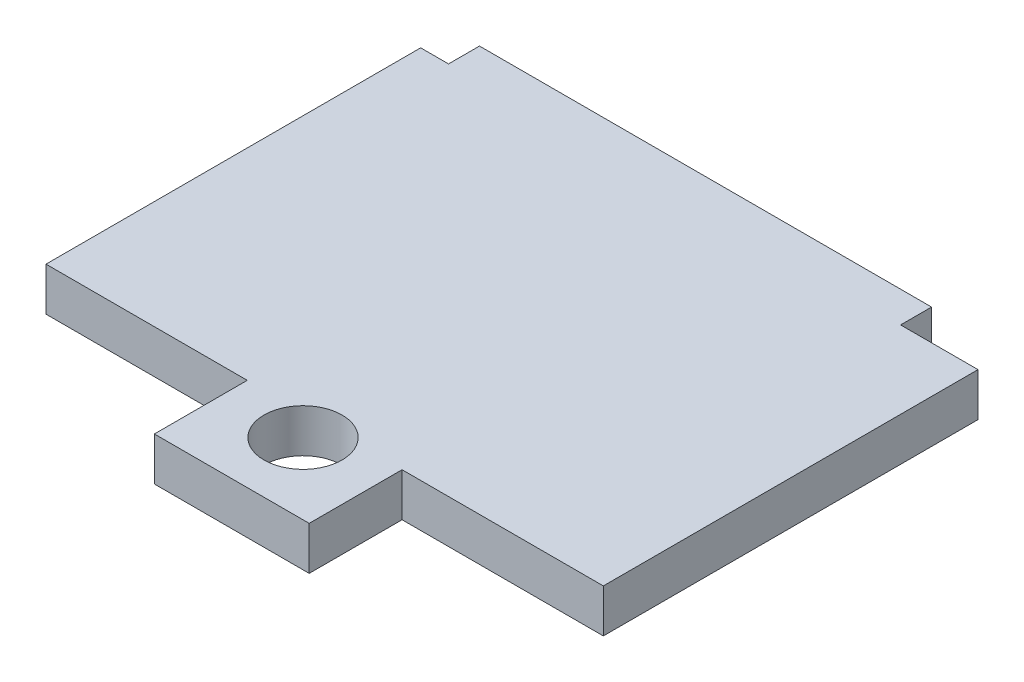
SolidWorks part; units mm, degrees
ref_plane "Front Plane" through (0, 0, 0) normal (0, 0, 1) x (1, 0, 0)
ref_plane "Top Plane" through (0, 0, 0) normal (0, 1, 0) x (1, 0, 0)
ref_plane "Right Plane" through (0, 0, 0) normal (1, 0, 0) x (0, 0, -1)
sketch "Sketch1" plane through (0, 0, 0) normal (0, 1, 0) x (1, 0, 0)
  line L0 (0, 15.367) -> (0, 0)
  line L1 (0, 0) -> (8.255, 0)
  line L2 (8.255, 0) -> (8.255, -3.81)
  line L3 (8.255, -3.81) -> (14.605, -3.81)
  line L4 (14.605, -3.81) -> (14.605, 0)
  line L5 (14.605, 0) -> (22.86, 0)
  line L6 (22.86, 0) -> (22.86, 15.367)
  line L8 (0, 15.367) -> (1.143, 15.367)
  line L9 (1.143, 15.367) -> (1.143, 16.637)
  line L10 (1.143, 16.637) -> (19.685, 16.637)
  line L11 (19.685, 16.637) -> (19.685, 15.367)
  line L12 (19.685, 15.367) -> (22.86, 15.367)
  dimension "D1" = 18.542
  dimension "D2" = 22.86
  dimension "D3" = 1.143
  dimension "D4" = 15.367
  dimension "D5" = 1.27
  dimension "D6" = 3.81
  dimension "D7" = 6.35
  dimension "D8" = 8.255
extrude "Boss-Extrude1" add sketch "Sketch1" along normal blind 1.778
hole_wizard "M3 Clearance Hole1" positions "Sketch2" profile "Sketch3" hole size "M3" standard "ANSI Metric" end condition through all
sketch "Sketch2" plane through (0, 1.778, 0) normal (0, 1, 0) x (1, 0, 0)
  line L0 (8.255, -3.81) -> (14.605, -3.81) construction
  line L1 (23.2514, 2.0338) -> (23.2514, -3.81) construction
  line L2 (12.3825, 2.0338) -> (23.495, 2.0338) construction
  point P0 (11.43, -0.8881)
  point P5 (11.43, -3.81)
  point P13 (23.2514, -0.8881)
sketch "Sketch3" plane through (11.43, 1.778, 0.8881) normal (1, 0, 0) x (0, 0, 1)
  line L0 (0, 0) -> (0, 1.778)
  line L1 (0, 1.778) -> (1.6, 1.778)
  line L2 (1.6, 1.778) -> (1.6, 0)
  line L5 (1.6, 0) -> (0, 0)
  line L11 (0, -6.35) -> (0, 107.95) construction
  dimension "Thru Hole Dia." = 3.2
  dimension "Thru Hole Depth" = 1.778
sketch "Sketch4" plane through (0, 0, 0) normal (0, -1, 0) x (1, 0, 0)
  line L1 (15.24, -4.3028) -> (17.78, -4.3028)
  line L2 (15.24, -4.3028) -> (15.24, -13.4468)
  line L3 (15.24, -13.4468) -> (17.78, -13.4468)
  line L4 (17.78, -4.3028) -> (17.78, -13.4468)
  line L5 (0, -4.3028) -> (2.54, -4.3028)
  line L6 (0, -4.3028) -> (0, -13.4468)
  line L7 (0, -13.4468) -> (2.54, -13.4468)
  line L8 (2.54, -4.3028) -> (2.54, -13.4468)
  line L9 (22.86, 0) -> (22.86, -15.367) construction
  line L10 (-0.635, -12.8914) -> (23.495, -12.8914) construction
  dimension "D1" = 9.144
  dimension "D2" = 2.54
  dimension "D3" = 12.7
  dimension "D4" = 5.08
  dimension "D5" = 0.5554
extrude "Boss-Extrude2" add sketch "Sketch4" along normal blind 1.143
sketch "Sketch6" plane through (0, 0, 0) normal (0, -1, 0) x (1, 0, 0)
  text T0 "<b>45</b>"
extrude "Cut-Extrude1" cut sketch "Sketch6" against normal blind 0.508
